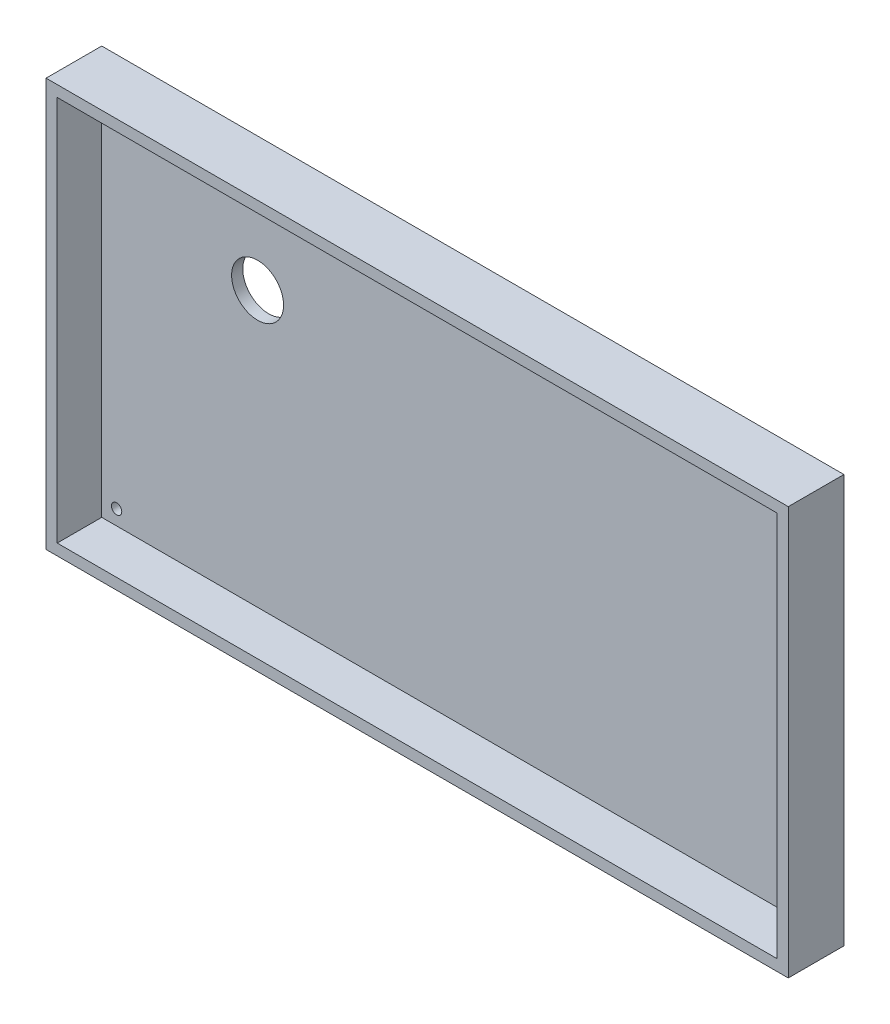
SolidWorks part; units mm, degrees
ref_plane "Front Plane" through (0, 0, 0) normal (0, 0, 1) x (1, 0, 0)
ref_plane "Top Plane" through (0, 0, 0) normal (0, 1, 0) x (1, 0, 0)
ref_plane "Right Plane" through (0, 0, 0) normal (1, 0, 0) x (0, 0, -1)
sketch "Sketch1" plane through (0, 0, 0) normal (0, 0, 1) x (1, 0, 0)
  line L1 (-96.0084, 31.3025) -> (103.9916, 31.3025)
  line L2 (-96.0084, 31.3025) -> (-96.0084, -78.6975)
  line L3 (-96.0084, -78.6975) -> (103.9916, -78.6975)
  line L4 (103.9916, 31.3025) -> (103.9916, -78.6975)
  dimension "D1" = 200
  dimension "D2" = 110
extrude "Boss-Extrude1" add sketch "Sketch1" along normal blind 3
sketch "Sketch2" plane through (0, 0, 3) normal (0, 0, 1) x (1, 0, 0)
  line L1 (-96.0084, 31.3025) -> (103.9916, 31.3025)
  line L2 (-96.0084, 31.3025) -> (-96.0084, -78.6975)
  line L3 (-96.0084, -78.6975) -> (103.9916, -78.6975)
  line L4 (103.9916, 31.3025) -> (103.9916, -78.6975)
  line L5 (-93.0084, 28.3025) -> (100.9916, 28.3025)
  line L6 (-93.0084, 28.3025) -> (-93.0084, -75.6975)
  line L7 (-93.0084, -75.6975) -> (100.9916, -75.6975)
  line L8 (100.9916, 28.3025) -> (100.9916, -75.6975)
  dimension "D1" = 3
  dimension "D2" = 3
  dimension "D3" = 3
  dimension "D4" = 3
extrude "Boss-Extrude2" add sketch "Sketch2" along normal blind 12
sketch "Sketch3" plane through (0, 0, 3) normal (0, 0, 1) x (1, 0, 0)
  line L0 (-93.0084, 28.3025) -> (-93.0084, -75.6975) construction
  line L1 (-93.0084, 28.3025) -> (-93.0084, -75.6975) construction
  line L2 (100.9916, -75.6975) -> (100.9916, 28.3025) construction
  line L3 (100.9916, 28.3025) -> (-93.0084, 28.3025) construction
  line L4 (100.9916, 28.3025) -> (-93.0084, 28.3025) construction
  line L5 (-93.0084, -75.6975) -> (100.9916, -75.6975) construction
  circle A0 centre (-89.0084, 24.3025) radius 1.4
  circle A1 centre (-89.0084, -71.6975) radius 1.4
  circle A2 centre (96.9916, 24.3025) radius 1.4
  circle A3 centre (96.9916, -71.6975) radius 1.4
  dimension "D1" = 2.8
  dimension "D2" = 2.8
  dimension "D3" = 2.8
  dimension "D4" = 2.8
  dimension "D10" = 4
  dimension "D5" = 4
  dimension "D6" = 4
  dimension "D7" = 4
  dimension "D8" = 4
  dimension "D9" = 4
  dimension "D11" = 4
  dimension "D12" = 4
extrude "Cut-Extrude2" cut sketch "Sketch3" against normal blind 3
sketch "Sketch5" plane through (0, 0, 3) normal (0, 0, 1) x (1, 0, 0)
  line L1 (-51.0084, 28.3025) -> (-51.0084, -75.6975) construction
  line L2 (100.9916, 28.3025) -> (-93.0084, 28.3025) construction
  line L3 (-93.0084, -75.6975) -> (100.9916, -75.6975) construction
  line L5 (-96.0084, 31.3025) -> (-96.0084, -78.6975) construction
  line L6 (-93.0084, -1.6975) -> (100.9916, -1.6975) construction
  line L7 (-93.0084, 28.3025) -> (-93.0084, -75.6975) construction
  line L8 (100.9916, -75.6975) -> (100.9916, 28.3025) construction
  circle A0 centre (-51.0084, -1.6975) radius 7
  dimension "D1" = 45
  dimension "D2" = 30
extrude "Cut-Extrude3" cut sketch "Sketch5" against normal blind 3
